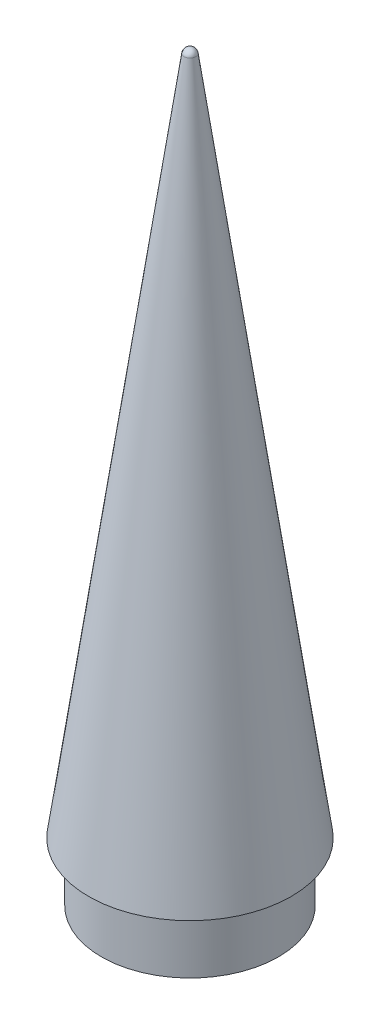
SolidWorks part; units mm, degrees
material "6061-T6 (SS)"
ref_plane "Front Plane" through (0, 0, 0) normal (0, 0, 1) x (1, 0, 0)
ref_plane "Top Plane" through (0, 0, 0) normal (0, 1, 0) x (1, 0, 0)
ref_plane "Right Plane" through (0, 0, 0) normal (1, 0, 0) x (0, 0, -1)
sketch "Sketch2" plane through (0, 0, 0) normal (0, 0, 1) x (1, 0, 0)
  line L0 (0, 168.7607) -> (21.9329, 12.7)
  line L1 (21.9329, 12.7) -> (19.177, 12.7)
  line L2 (19.177, 12.7) -> (19.177, 0)
  line L3 (19.177, 0) -> (0, 0)
  line L4 (0, 0) -> (0, 168.7607)
  arc A0 (0, 160.9054) -> (1.2576, 159.8121) centre (0, 159.6354) cw
  dimension "D5" = 1.27
  dimension "D1" = 19.177
  dimension "D2" = 21.9329
  dimension "D3" = 8
  dimension "D4" = 12.7
revolve "Revolve1" add sketch "Sketch2" angle 360 about L4
sketch "Sketch3" plane through (0, 0, 0) normal (0, -1, 0) x (1, 0, 0)
  point P0 (0, 0)
hole_wizard "Tap Drill for 1/4-20 Tap1" positions "Sketch5" profile "Sketch7" hole size "1/4-20" standard "ANSI Inch"
sketch "Sketch5" plane through (0, 0, 0) normal (0, -1, 0) x (-1, 0, 0)
  point P0 (0, 0)
sketch "Sketch7" plane through (0, 0, 0) normal (1, 0, 0) x (0, 0, -1)
  line L0 (0, 0) -> (0, 20.5838)
  line L1 (0, 20.5838) -> (2.5527, 19.05)
  line L2 (2.5527, 19.05) -> (2.5527, 0)
  line L5 (2.5527, 0) -> (0, 0)
  line L10 (0, 20.5838) -> (-2.5527, 19.05) construction
  line L11 (0, -6.35) -> (0, 107.95) construction
  dimension "Hole Dia." = 5.1054
  dimension "Hole Depth" = 19.05
  dimension "Drill Angle" = 118
